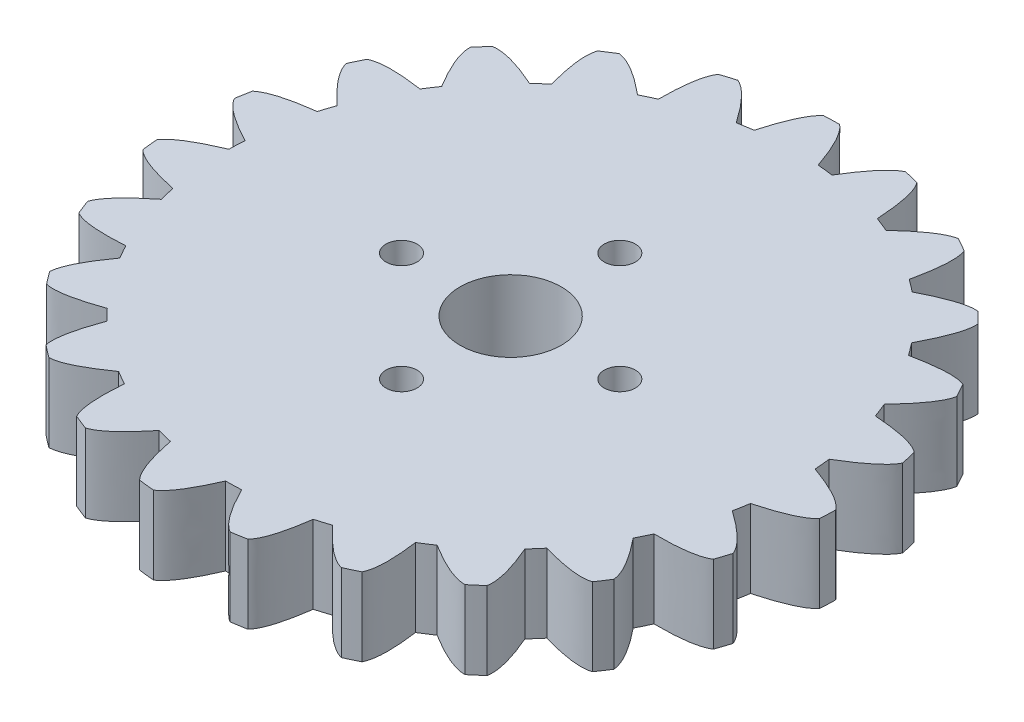
SolidWorks part; units mm, degrees
material "ABS"
ref_plane "Front Plane" through (0, 0, 0) normal (0, 0, 1) x (1, 0, 0)
ref_plane "Top Plane" through (0, 0, 0) normal (0, 1, 0) x (1, 0, 0)
ref_plane "Right Plane" through (0, 0, 0) normal (1, 0, 0) x (0, 0, -1)
sketch "Sketch1" plane through (0, 0, 0) normal (0, 1, 0) x (1, 0, 0)
  line L0 (11.5353, 14.2102) -> (14.3418, 11.3712) construction
  line L2 (12.9386, 12.7907) -> (15.072, 14.8998) construction
  line L3 (15.072, 14.8998) -> (15.2104, 15.0366)
  circle A0 centre (0, 0) radius 18.3028
  circle A1 centre (0, 0) radius 21.1937
  spline S0 degree 2 poles (14.3418, 11.3712) (17.4822, 17.2825) (11.5353, 14.2102) knots 0 0 0 1 1 1
  point P3 (11.5353, 14.2102)
  point P4 (14.3418, 11.3712)
  point P6 (14.7163, 15.2512)
  point P12 (10.7421, 14.8189)
  point P14 (15.2104, 15.0366)
  point P15 (15.4194, 14.5401)
  point P16 (7.7366, 16.5873)
  dimension "D1" = 36.6056
  dimension "D4" = 3
  dimension "D5" = 1
  dimension "D2" = 4
  dimension "D3" = 1
extrude "Boss-Extrude4" add sketch "Sketch1" along normal blind 5 contours A0 | A0 S0 A1
pattern_circular "CirPattern6" count 23 every 15.652 about axis through (0, 5, 0) along (0, 1, 0) of "Boss-Extrude4"
sketch "Sketch2" plane through (0, 5, 0) normal (0, 1, 0) x (1, 0, 0)
  circle A0 centre (0, 0) radius 3.25
  dimension "D1" = 6.5
extrude "Cut-Extrude1" cut sketch "Sketch2" against normal blind 10
sketch "Sketch5" plane through (0, 5, 0) normal (0, 1, 0) x (1, 0, 0)
  circle A0 centre (0, 0) radius 3.25 construction
  circle A1 centre (7, 0) radius 1
  dimension "D1" = 2
  dimension "D2" = 7
extrude "Cut-Extrude2" cut sketch "Sketch5" against normal blind 10
pattern_circular "CirPattern7" count 4 over 360 about axis through (0, 0, 0) along (0, 1, 0) of "Cut-Extrude2"
equation "\"number-of-teeth\"= 23"
equation "\"gear-size\"= 4mm"
equation "\"circumference\"= \"number-of-teeth\" * ( ( 1 + \"space-between-teeth\" ) * \"gear-size\" )"
equation "\"space-between-teeth\"= .25"
equation "\"D1@Sketch1\" = \"circumference\" / pi"
equation "\"D2@Sketch1\"=\"gear-size\""
equation "\"gear-length\"= 3mm"
equation "\"D4@Sketch1\"=\"gear-length\""
equation "\"D5@Sketch1\"=\"gear-size\" * \"space-between-teeth\""
equation "\"D3@Sketch1\"=\"gear-size\" * \"space-between-teeth\""
equation "\"D1@CirPattern6\"=\"number-of-teeth\""
equation "\"D2@CirPattern6\"=360 / \"number-of-teeth\""
